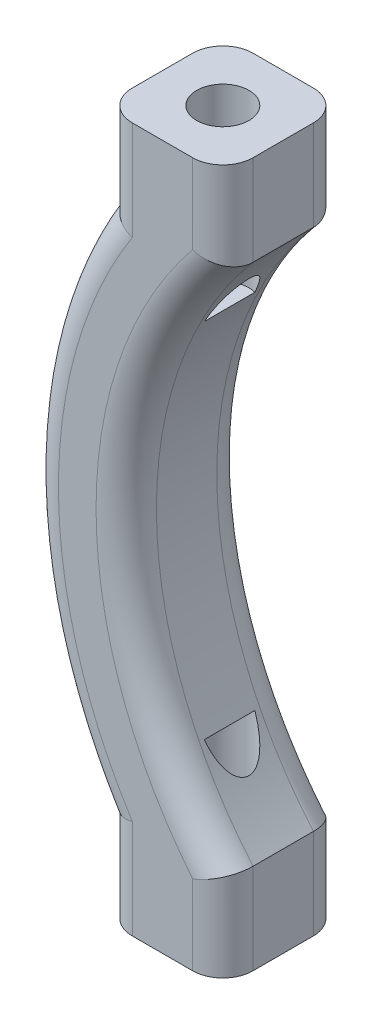
SolidWorks part; units mm, degrees
ref_plane "Front Plane" through (0, 0, 0) normal (0, 0, 1) x (1, 0, 0)
ref_plane "Top Plane" through (0, 0, 0) normal (0, 1, 0) x (1, 0, 0)
ref_plane "Right Plane" through (0, 0, 0) normal (1, 0, 0) x (0, 0, -1)
sketch "Sketch1" plane through (0, 0, 0) normal (0, 0, 1) x (1, 0, 0)
  line L0 (-4.8013, -2.3677) -> (1.1987, -2.3677)
  line L1 (1.1987, -2.3677) -> (1.1987, 2.1323)
  line L3 (1.1987, 2.1323) -> (-4.8013, 2.1323)
  line L4 (1.1987, 2.1323) -> (1.1987, -2.3677)
  line L5 (1.1987, -2.3677) -> (-4.8013, -2.3677)
  line L6 (-4.8013, 2.1323) -> (-4.8013, -2.3677)
  line L7 (1.1987, 28.1323) -> (1.1987, 32.6323)
  line L9 (1.1987, 32.6323) -> (-4.8013, 32.6323)
  line L10 (1.1987, 32.6323) -> (1.1987, 28.1323)
  line L11 (1.1987, 28.1323) -> (-4.8013, 28.1323)
  line L12 (-4.8013, 32.6323) -> (-4.8013, 28.1323)
  circle A0 centre (16.3974, 15.1323) radius 20 construction
  arc A1 (1.1987, 2.1323) -> (1.1987, 28.1323) centre (16.3974, 15.1323) cw
  arc A2 (-4.8013, 28.1323) -> (-4.8013, 2.1323) centre (16.3974, 15.1323) ccw
  dimension "D3" = 40
  dimension "D1" = 6
  dimension "D2" = 4.5
  dimension "D4" = 35
extrude "Boss-Extrude1" add sketch "Sketch1" along normal blind 6 contours L11 A2 L3 A1 | L9 L12 L11 L7 | L3 L6 L0 L1
sketch "Sketch2" plane through (0, -2.3677, 0) normal (0, -1, 0) x (1, 0, 0)
  line L1 (1.1987, 6) -> (1.1987, 0) construction
  line L2 (1.1987, 3) -> (-4.8013, 3) construction
  line L3 (-4.8013, 6) -> (-4.8013, 0) construction
  point P0 (-1.8013, 3)
sketch "Sketch3" plane through (0, 32.6323, 0) normal (0, 1, 0) x (1, 0, 0)
  line L0 (-4.8013, -3) -> (1.1987, -3) construction
  line L1 (-4.8013, -6) -> (-4.8013, 0) construction
  line L2 (1.1987, -6) -> (1.1987, 0) construction
  point P6 (-1.8013, -3)
hole_wizard "Hole1" positions "3DSketch1" profile "Sketch4" legacy
sketch3d "3DSketch1"
  point P0 (-1.8013, 32.6323, 3)
  point P3 (-1.8013, -2.3677, 3)
sketch "Sketch4" plane through (-1.8013, 32.6323, 3) normal (1, 0, 0) x (0, 0, 1)
  line L0 (0, 0) -> (0, 8.5)
  line L1 (0, 8.5) -> (1.3, 8.5)
  line L2 (1.3, 8.5) -> (1.3, 0)
  line L3 (1.3, 0) -> (0, 0)
  line L4 (0, 110) -> (0, -10) construction
  dimension "Diameter" = 2.6
  dimension "Depth" = 8.5
fillet "Fillet1" radius 1.5 12 edges at (-8.4699, 15.1323, 0) (-8.4699, 15.1323, 6) (-3.6026, 15.1323, 0) (-3.6026, 15.1323, 6) (-4.8013, -0.1177, 0) (-4.8013, -0.1177, 6) (1.1987, -0.1177, 0) (1.1987, -0.1177, 6) (1.1987, 30.3823, 0) (1.1987, 30.3823, 6) (-4.8013, 30.3823, 0) (-4.8013, 30.3823, 6)
